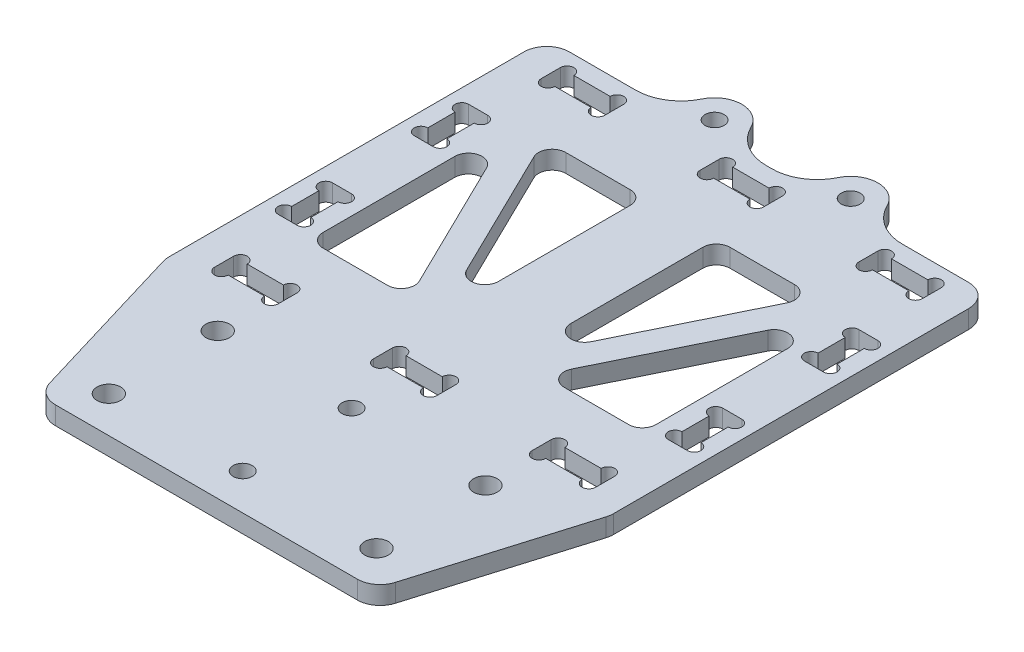
SolidWorks part; units mm, degrees
ref_plane "前视基准面" through (0, 0, 0) normal (0, 0, 1) x (1, 0, 0)
ref_plane "上视基准面" through (0, 0, 0) normal (0, 1, 0) x (1, 0, 0)
ref_plane "右视基准面" through (0, 0, 0) normal (1, 0, 0) x (0, 0, -1)
other "Configuration Table"
sketch "草图1" plane through (0, 0, 0) normal (0, 1, 0) x (1, 0, 0)
  line L0 (-37, 0) -> (37, 0)
  line L1 (37, 0) -> (37, 40)
  line L2 (37, 40) -> (49, 40)
  line L3 (49, 40) -> (49, 124)
  line L4 (0, 0) -> (0, 122.7817) construction
  line L5 (49, 124) -> (-49, 124)
  line L6 (-49, 40) -> (-49, 124)
  line L7 (-37, 40) -> (-49, 40)
  line L8 (-37, 0) -> (-37, 40)
  point P10 (0, 124)
  point P13 (0, 0)
  dimension "D1" = 74
  dimension "D2" = 40
  dimension "D3" = 84
  dimension "D4" = 98
extrude "凸台-拉伸1" add sketch "草图1" along normal blind 4
sketch "草图2" plane through (0, 4, 0) normal (0, 1, 0) x (1, 0, 0)
  line L0 (0, 0) -> (0, 124) construction
  line L1 (-37, 0) -> (37, 0) construction
  line L2 (49, 124) -> (-49, 124) construction
  line L3 (-37, 20) -> (37, 20) construction
  circle A0 centre (29.5, 8) radius 2.6
  circle A1 centre (-29.5, 8) radius 2.6
  circle A2 centre (29.5, 32) radius 2.6
  circle A3 centre (-29.5, 32) radius 2.6
  circle A4 centre (0, 32) radius 2.1
  circle A5 centre (0, 8) radius 2.1
  dimension "D1" = 59
  dimension "D3" = 24
  dimension "D4" = 5.2
  dimension "D5" = 4.2
  dimension "D2" = 20
extrude "切除-拉伸1" cut sketch "草图2" against normal blind 4
sketch "草图3" plane through (0, 4, 0) normal (0, 1, 0) x (1, 0, 0)
  line L19 (-49, 81.9) -> (49, 81.9) construction
  line L20 (-49, 124) -> (-49, 40) construction
  line L21 (49, 40) -> (49, 124) construction
  line L22 (-7, 43.8) -> (7, 48) construction
  line L23 (-7, 48) -> (7, 43.8) construction
  line L24 (0, 0) -> (0, 124) construction
  line L25 (-37, 0) -> (37, 0) construction
  line L26 (49, 124) -> (-49, 124) construction
  line L28 (-7, 115.8) -> (7, 115.8)
  line L29 (-7, 115.8) -> (-7, 120)
  line L30 (-7, 120) -> (7, 120)
  line L31 (7, 115.8) -> (7, 120)
  line L32 (-7, 115.8) -> (7, 120) construction
  line L33 (-7, 120) -> (7, 115.8) construction
  line L46 (28, 115.8) -> (42, 115.8)
  line L47 (28, 115.8) -> (28, 120)
  line L48 (28, 120) -> (42, 120)
  line L49 (42, 115.8) -> (42, 120)
  line L58 (-42, 115.8) -> (-42, 120)
  line L59 (-28, 120) -> (-42, 120)
  line L60 (-28, 115.8) -> (-28, 120)
  line L61 (-28, 115.8) -> (-42, 115.8)
  line L62 (-28, 48) -> (-42, 48)
  line L63 (-28, 48) -> (-28, 43.8)
  line L64 (-28, 43.8) -> (-42, 43.8)
  line L65 (-42, 48) -> (-42, 43.8)
  line L66 (42, 48) -> (42, 43.8)
  line L67 (28, 43.8) -> (42, 43.8)
  line L68 (28, 48) -> (28, 43.8)
  line L69 (28, 48) -> (42, 48)
  line L70 (7, 48) -> (7, 43.8)
  line L71 (-7, 43.8) -> (7, 43.8)
  line L72 (-7, 48) -> (-7, 43.8)
  line L73 (-7, 48) -> (7, 48)
  line L74 (-42, 117.9) -> (-28, 117.9) construction
  circle A0 centre (-5.5, 120) radius 1.5
  circle A1 centre (-5.5, 115.8) radius 1.5
  circle A2 centre (5.5, 120) radius 1.5
  circle A3 centre (5.5, 115.8) radius 1.5
  circle A4 centre (29.5, 115.8) radius 1.5
  circle A5 centre (29.5, 120) radius 1.5
  circle A6 centre (40.5, 120) radius 1.5
  circle A7 centre (40.5, 115.8) radius 1.5
  circle A16 centre (-40.5, 115.8) radius 1.5
  circle A17 centre (-40.5, 120) radius 1.5
  circle A18 centre (-29.5, 120) radius 1.5
  circle A19 centre (-29.5, 115.8) radius 1.5
  circle A20 centre (-29.5, 48) radius 1.5
  circle A21 centre (-29.5, 43.8) radius 1.5
  circle A22 centre (-40.5, 43.8) radius 1.5
  circle A23 centre (-40.5, 48) radius 1.5
  circle A24 centre (40.5, 48) radius 1.5
  circle A25 centre (40.5, 43.8) radius 1.5
  circle A26 centre (29.5, 43.8) radius 1.5
  circle A27 centre (29.5, 48) radius 1.5
  circle A28 centre (5.5, 48) radius 1.5
  circle A29 centre (5.5, 43.8) radius 1.5
  circle A30 centre (-5.5, 48) radius 1.5
  circle A31 centre (-5.5, 43.8) radius 1.5
  point P6 (0, 117.9)
  point P85 (0, 45.9)
  dimension "D4" = 3
  dimension "D1" = 14
  dimension "D2" = 4.2
  dimension "D3" = 4
  dimension "D6" = 35
  dimension "D5" = 2
  dimension "D7" = 36
extrude "切除-拉伸2" cut sketch "草图3" against normal blind 4 contours L30 A0 | A3 L31 A2 L30 A0 L29 A1 L28 | L30 A0 | L28 A1 | L28 A1 | L30 A2 | L30 A2 | L28 A3 | L28 A3
sketch "草图4" plane through (0, 4, 0) normal (0, 1, 0) x (1, 0, 0)
  line L0 (-49, 40) -> (-37, 0)
  line L6 (0, 0) -> (0, 124) construction
  line L7 (-37, 0) -> (37, 0) construction
  line L8 (49, 124) -> (-49, 124) construction
  line L12 (49, 40) -> (37, 0)
  line L13 (-49, 40) -> (-37, 40)
  line L14 (-37, 40) -> (-37, 0)
  line L15 (37, 0) -> (37, 40)
  line L16 (37, 40) -> (49, 40)
extrude "凸台-拉伸2" add sketch "草图4" against normal blind 4
sketch "草图5" plane through (0, 4, 0) normal (0, 1, 0) x (1, 0, 0)
  line L1 (0, 120) -> (0, 88.6773) construction
  line L2 (-4, 120) -> (4, 120) construction
  line L3 (-28, 115.8) -> (-28, 120) construction
  line L4 (49, 124) -> (-49, 124) construction
  circle A1 centre (-15, 127) radius 6
  circle A2 centre (-15, 127) radius 2.1
  circle A3 centre (15, 127) radius 6
  circle A4 centre (15, 127) radius 2.1
  dimension "D1" = 4.2
  dimension "D3" = 3
  dimension "D4" = 12
  dimension "D2" = 13
  dimension "D5" = 2
extrude "凸台-拉伸3" add sketch "草图5" against normal blind 4
fillet "圆角1" radius 10 4 edges at (-9.8038, 2, -124) (-20.1962, 2, -124) (20.1962, 2, -124) (9.8038, 2, -124)
sketch "草图6" plane through (0, 4, 0) normal (0, 1, 0) x (1, 0, 0)
  line L0 (39, 115.8) -> (39, 48) construction
  line L1 (39, 81.9) -> (96.5672, 81.9) construction
  line L3 (45.1, 60.9) -> (45.1, 72.9)
  line L4 (40.9, 102.9) -> (45.1, 102.9)
  line L5 (40.9, 102.9) -> (40.9, 90.9)
  line L6 (40.9, 90.9) -> (45.1, 90.9)
  line L7 (45.1, 102.9) -> (45.1, 90.9)
  line L8 (40.9, 72.9) -> (45.1, 72.9)
  line L9 (40.9, 60.9) -> (40.9, 72.9)
  line L10 (40.9, 60.9) -> (45.1, 60.9)
  line L11 (43, 102.9) -> (43, 90.9) construction
  line L12 (49, 40) -> (49, 124) construction
  circle A0 centre (40.9, 101.4) radius 1.5
  circle A1 centre (45.1, 101.4) radius 1.5
  circle A2 centre (40.9, 92.4) radius 1.5
  circle A3 centre (45.1, 92.4) radius 1.5
  circle A4 centre (45.1, 71.4) radius 1.5
  circle A5 centre (40.9, 71.4) radius 1.5
  circle A6 centre (40.9, 62.4) radius 1.5
  circle A7 centre (45.1, 62.4) radius 1.5
  dimension "D5" = 3
  dimension "D1" = 12
  dimension "D2" = 4.2
  dimension "D3" = 18
  dimension "D4" = 6
extrude "切除-拉伸3" cut sketch "草图6" against normal blind 10 contours A6 L9 | L10 A7 L3 A4 L8 A5 L9 A6 | A6 L9 | A7 L3 | A7 L3 | A4 L3 | A4 L3 | A5 L9 | A5 L9 | L5 A2 | L5 A0 | L5 A2 | A3 L7 A1 L4 A0 L5 A2 L6 | L7 A3 | L7 A1 | L7 A1 | L5 A0 | L7 A3
sketch "草图7" plane through (0, 4, 0) normal (0, 1, 0) x (1, 0, 0)
  line L0 (-36.6787, 104.4) -> (-36.6787, 59.4)
  line L1 (-36.6787, 59.4) -> (-14.6787, 59.4)
  line L2 (-14.6787, 59.4) -> (-36.6787, 104.4)
  line L3 (-30, 104.4) -> (-8, 59.4)
  line L4 (-8, 59.4) -> (-8, 104.4)
  line L5 (-8, 104.4) -> (-30, 104.4)
  line L6 (0, 115.8) -> (0, 48) construction
  line L7 (-4, 115.8) -> (4, 115.8) construction
  line L8 (-4, 48) -> (4, 48) construction
  line L9 (8, 104.4) -> (30, 104.4)
  line L10 (8, 59.4) -> (8, 104.4)
  line L11 (30, 104.4) -> (8, 59.4)
  line L12 (14.6787, 59.4) -> (36.6787, 104.4)
  line L13 (36.6787, 59.4) -> (14.6787, 59.4)
  line L14 (36.6787, 104.4) -> (36.6787, 59.4)
  line L15 (0, 81.9) -> (13.1956, 81.9) construction
  dimension "D1" = 22
  dimension "D2" = 45
  dimension "D3" = 6
  dimension "D4" = 16
extrude "切除-拉伸4" cut sketch "草图7" against normal blind 5
fillet "圆角3" radius 3 12 edges at (14.6787, 2, -59.4) (36.6787, 2, -59.4) (30, 2, -104.4) (8, 2, -104.4) (36.6787, 2, -104.4) (8, 2, -59.4) (-8, 2, -104.4) (-30, 2, -104.4) (-8, 2, -59.4) (-14.6787, 2, -59.4) (-36.6787, 2, -59.4) (-36.6787, 2, -104.4)
mirror "镜向1" about plane through (0, 0, 0) normal (1, 0, 0) of "切除-拉伸3"
fillet "圆角4" radius 5 6 edges at (37, 2, 0) (-37, 2, 0) (-49, 2, -40) (49, 2, -40) (49, 2, -124) (-49, 2, -124)
